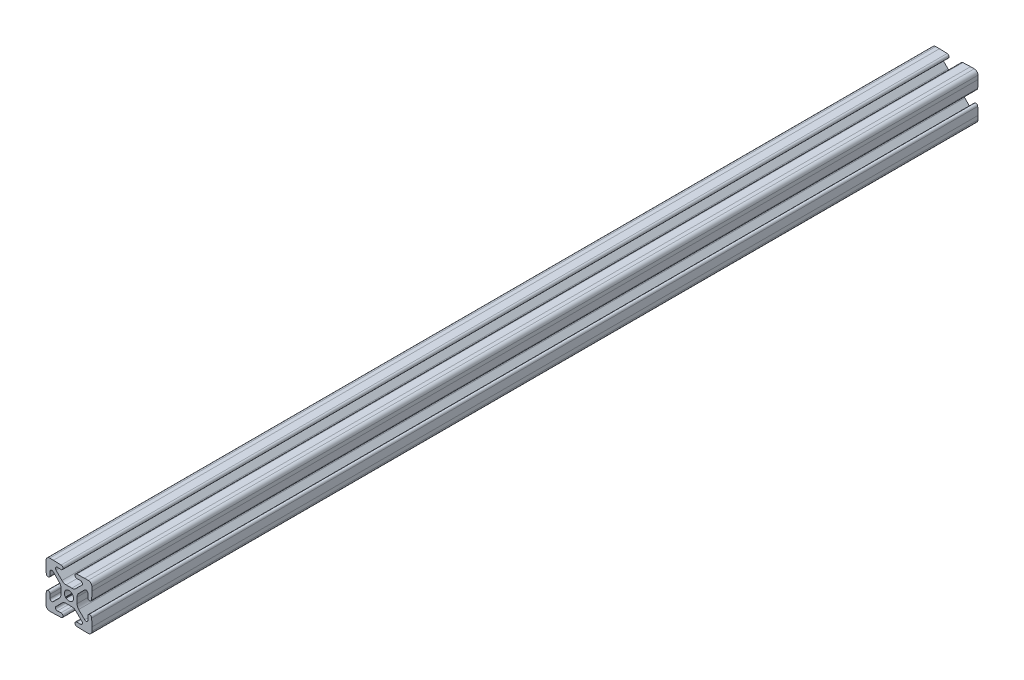
SolidWorks part; units mm, degrees
ref_plane "Front Plane" through (0, 0, 0) normal (0, 0, 1) x (1, 0, 0)
ref_plane "Top Plane" through (0, 0, 0) normal (0, 1, 0) x (1, 0, 0)
ref_plane "Right Plane" through (0, 0, 0) normal (1, 0, 0) x (0, 0, -1)
sketch "Model" plane through (0, 0, 0) normal (0, 0, 1) x (1, 0, 0)
  line L38 (50.6495, 75.4336) -> (50.2699, 75.4336)
  line L39 (50.2699, 75.4336) -> (50.2699, 75.8133)
  line L40 (50.66, 72.9999) -> (53.7746, 72.9999)
  line L41 (56.0196, 72.0699) -> (59.2642, 68.8254)
  line L42 (58.5103, 67.0916) -> (56.5725, 67.1592)
  line L43 (56.498, 65.0269) -> (60.6773, 64.881)
  line L44 (60.6773, 64.881) -> (62.7107, 64.881)
  line L45 (64.7173, 66.8876) -> (64.7173, 68.921)
  line L46 (64.7173, 68.921) -> (64.5713, 73.1002)
  line L47 (62.439, 73.0257) -> (62.5067, 71.0879)
  line L48 (60.7729, 70.334) -> (57.5283, 73.5786)
  line L49 (56.5984, 75.8237) -> (56.5984, 78.9383)
  line L50 (57.5283, 81.1833) -> (60.7729, 84.4279)
  line L51 (62.5067, 83.674) -> (62.439, 81.7362)
  line L52 (64.5713, 81.6617) -> (64.7173, 85.841)
  line L53 (64.7173, 85.841) -> (64.7173, 87.8744)
  line L54 (62.7107, 89.881) -> (60.6773, 89.881)
  line L55 (60.6773, 89.881) -> (56.498, 89.735)
  line L56 (56.5725, 87.6027) -> (58.5103, 87.6704)
  line L57 (59.2642, 85.9366) -> (56.0196, 82.692)
  line L58 (53.7746, 81.7621) -> (50.66, 81.7621)
  line L59 (48.4149, 82.692) -> (45.1703, 85.9366)
  line L60 (45.9242, 87.6704) -> (47.862, 87.6027)
  line L61 (47.9365, 89.735) -> (43.7573, 89.881)
  line L62 (43.7573, 89.881) -> (41.7239, 89.881)
  line L63 (39.7173, 87.8744) -> (39.7173, 85.841)
  line L64 (39.7173, 85.841) -> (39.8632, 81.6617)
  line L65 (41.9955, 81.7362) -> (41.9278, 83.674)
  line L66 (43.6616, 84.4279) -> (46.9062, 81.1833)
  line L67 (47.8361, 78.9383) -> (47.8361, 75.8237)
  line L68 (46.9062, 73.5786) -> (43.6616, 70.334)
  line L69 (41.9278, 71.0879) -> (41.9955, 73.0257)
  line L70 (39.8632, 73.1002) -> (39.7173, 68.921)
  line L71 (39.7173, 68.921) -> (39.7173, 66.8876)
  line L72 (41.7239, 64.881) -> (43.7573, 64.881)
  line L73 (43.7573, 64.881) -> (47.9365, 65.0269)
  line L74 (47.862, 67.1592) -> (45.9242, 67.0916)
  line L75 (45.1703, 68.8254) -> (48.4149, 72.0699)
  arc A29 (50.6495, 75.4336) -> (50.2699, 75.8133) centre (52.2173, 77.381) ccw
  arc A30 (56.0196, 72.0699) -> (53.7746, 72.9999) centre (53.7746, 69.8249) ccw
  arc A31 (58.5103, 67.0916) -> (59.2642, 68.8254) centre (58.5458, 68.1069) ccw
  arc A32 (56.5725, 67.1592) -> (56.498, 65.0269) centre (56.5353, 66.0931) ccw
  arc A33 (62.7107, 64.881) -> (64.7173, 66.8876) centre (62.7107, 66.8876) ccw
  arc A34 (64.5713, 73.1002) -> (62.439, 73.0257) centre (63.5052, 73.063) ccw
  arc A35 (60.7729, 70.334) -> (62.5067, 71.0879) centre (61.4913, 71.0525) ccw
  arc A36 (56.5984, 75.8237) -> (57.5283, 73.5786) centre (59.7734, 75.8237) ccw
  arc A37 (57.5283, 81.1833) -> (56.5984, 78.9383) centre (59.7734, 78.9383) ccw
  arc A38 (62.5067, 83.674) -> (60.7729, 84.4279) centre (61.4913, 83.7095) ccw
  arc A39 (62.439, 81.7362) -> (64.5713, 81.6617) centre (63.5052, 81.699) ccw
  arc A40 (64.7173, 87.8744) -> (62.7107, 89.881) centre (62.7107, 87.8744) ccw
  arc A41 (56.498, 89.735) -> (56.5725, 87.6027) centre (56.5353, 88.6689) ccw
  arc A42 (59.2642, 85.9366) -> (58.5103, 87.6704) centre (58.5458, 86.655) ccw
  arc A43 (53.7746, 81.7621) -> (56.0196, 82.692) centre (53.7746, 84.9371) ccw
  arc A44 (48.4149, 82.692) -> (50.66, 81.7621) centre (50.66, 84.9371) ccw
  arc A45 (45.9242, 87.6704) -> (45.1703, 85.9366) centre (45.8887, 86.655) ccw
  arc A46 (47.862, 87.6027) -> (47.9365, 89.735) centre (47.8993, 88.6689) ccw
  arc A47 (41.7239, 89.881) -> (39.7173, 87.8744) centre (41.7239, 87.8744) ccw
  arc A48 (39.8632, 81.6617) -> (41.9955, 81.7362) centre (40.9293, 81.699) ccw
  arc A49 (43.6616, 84.4279) -> (41.9278, 83.674) centre (42.9432, 83.7095) ccw
  arc A50 (47.8361, 78.9383) -> (46.9062, 81.1833) centre (44.6611, 78.9383) ccw
  arc A51 (46.9062, 73.5786) -> (47.8361, 75.8237) centre (44.6611, 75.8237) ccw
  arc A52 (41.9278, 71.0879) -> (43.6616, 70.334) centre (42.9432, 71.0525) ccw
  arc A53 (41.9955, 73.0257) -> (39.8632, 73.1002) centre (40.9293, 73.063) ccw
  arc A54 (39.7173, 66.8876) -> (41.7239, 64.881) centre (41.7239, 66.8876) ccw
  arc A55 (47.9365, 65.0269) -> (47.862, 67.1592) centre (47.8993, 66.0931) ccw
  arc A56 (45.1703, 68.8254) -> (45.9242, 67.0916) centre (45.8887, 68.1069) ccw
  arc A57 (50.66, 72.9999) -> (48.4149, 72.0699) centre (50.66, 69.8249) ccw
extrude "Boss-Extrude1" add sketch "Model" along normal blind 482.219
